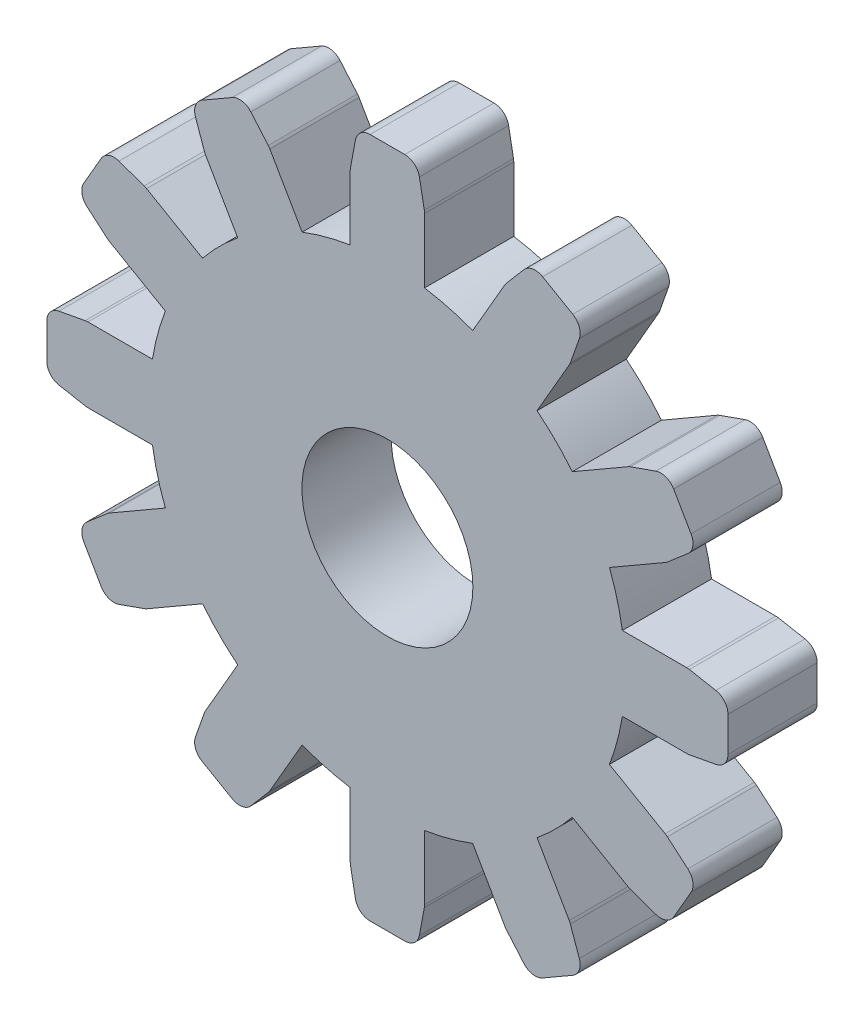
SolidWorks part; units mm, degrees
ref_plane "Front Plane" through (0, 0, 0) normal (0, 0, 1) x (1, 0, 0)
ref_plane "Top Plane" through (0, 0, 0) normal (0, 1, 0) x (1, 0, 0)
ref_plane "Right Plane" through (0, 0, 0) normal (1, 0, 0) x (0, 0, -1)
sketch "Sketch1" plane through (0, 0, 0) normal (0, 0, 1) x (1, 0, 0)
  line L0 (0, 0) -> (14.9711, 0) construction
  line L1 (0, 0) -> (0, 29.8184) construction
  line L2 (-1, 11.4548) -> (1, 11.4548)
  line L4 (-1.25, 10.1102) -> (-1.25, 7.9017)
  line L6 (1.25, 10.1187) -> (1.25, 7.9017)
  line L7 (3.9726, 9.3807) -> (2.8683, 7.4681)
  line L8 (4.8614, 10.4202) -> (3.9726, 9.3807)
  line L9 (-1, 11.4548) -> (-1.25, 10.1102)
  line L10 (1, 11.4548) -> (1.25, 10.1187)
  line L11 (4.8614, 10.4202) -> (6.5934, 9.4202)
  line L12 (6.5934, 9.4202) -> (6.1419, 8.1381)
  line L13 (6.1419, 8.1381) -> (5.0334, 6.2181)
  line L14 (8.1307, 6.1376) -> (6.2181, 5.0334)
  line L15 (9.4202, 6.5934) -> (8.1307, 6.1376)
  line L16 (9.4202, 6.5934) -> (10.4202, 4.8614)
  line L17 (10.4202, 4.8614) -> (9.3881, 3.9768)
  line L18 (9.3881, 3.9768) -> (7.4681, 2.8683)
  line L19 (10.1102, 1.25) -> (7.9017, 1.25)
  line L20 (11.4548, 1) -> (10.1102, 1.25)
  line L21 (11.4548, 1) -> (11.4548, -1)
  line L22 (11.4548, -1) -> (10.1187, -1.25)
  line L23 (10.1187, -1.25) -> (7.9017, -1.25)
  line L24 (9.3807, -3.9726) -> (7.4681, -2.8683)
  line L25 (10.4202, -4.8614) -> (9.3807, -3.9726)
  line L26 (10.4202, -4.8614) -> (9.4202, -6.5934)
  line L27 (9.4202, -6.5934) -> (8.1381, -6.1419)
  line L28 (8.1381, -6.1419) -> (6.2181, -5.0334)
  line L29 (6.1376, -8.1307) -> (5.0334, -6.2181)
  line L30 (6.5934, -9.4202) -> (6.1376, -8.1307)
  line L31 (6.5934, -9.4202) -> (4.8614, -10.4202)
  line L32 (4.8614, -10.4202) -> (3.9768, -9.3881)
  line L33 (3.9768, -9.3881) -> (2.8683, -7.4681)
  line L34 (1.25, -10.1102) -> (1.25, -7.9017)
  line L35 (1, -11.4548) -> (1.25, -10.1102)
  line L36 (1, -11.4548) -> (-1, -11.4548)
  line L37 (-1, -11.4548) -> (-1.25, -10.1187)
  line L38 (-1.25, -10.1187) -> (-1.25, -7.9017)
  line L39 (-3.9726, -9.3807) -> (-2.8683, -7.4681)
  line L40 (-4.8614, -10.4202) -> (-3.9726, -9.3807)
  line L41 (-4.8614, -10.4202) -> (-6.5934, -9.4202)
  line L42 (-6.5934, -9.4202) -> (-6.1419, -8.1381)
  line L43 (-6.1419, -8.1381) -> (-5.0334, -6.2181)
  line L44 (-8.1307, -6.1376) -> (-6.2181, -5.0334)
  line L45 (-9.4202, -6.5934) -> (-8.1307, -6.1376)
  line L46 (-9.4202, -6.5934) -> (-10.4202, -4.8614)
  line L47 (-10.4202, -4.8614) -> (-9.3881, -3.9768)
  line L48 (-9.3881, -3.9768) -> (-7.4681, -2.8683)
  line L49 (-10.1102, -1.25) -> (-7.9017, -1.25)
  line L50 (-11.4548, -1) -> (-10.1102, -1.25)
  line L51 (-11.4548, -1) -> (-11.4548, 1)
  line L52 (-11.4548, 1) -> (-10.1187, 1.25)
  line L53 (-10.1187, 1.25) -> (-7.9017, 1.25)
  line L54 (-9.3807, 3.9726) -> (-7.4681, 2.8683)
  line L55 (-10.4202, 4.8614) -> (-9.3807, 3.9726)
  line L56 (-10.4202, 4.8614) -> (-9.4202, 6.5934)
  line L57 (-9.4202, 6.5934) -> (-8.1381, 6.1419)
  line L58 (-8.1381, 6.1419) -> (-6.2181, 5.0334)
  line L59 (-6.1376, 8.1307) -> (-5.0334, 6.2181)
  line L60 (-6.5934, 9.4202) -> (-6.1376, 8.1307)
  line L61 (-6.5934, 9.4202) -> (-4.8614, 10.4202)
  line L62 (-4.8614, 10.4202) -> (-3.9768, 9.3881)
  line L63 (-3.9768, 9.3881) -> (-2.8683, 7.4681)
  arc A0 (2.8683, 7.4681) -> (1.25, 7.9017) centre (0, 0) ccw
  circle A1 centre (0, 0) radius 2.875
  arc A2 (-1.25, 7.9017) -> (-2.8683, 7.4681) centre (0, 0) ccw
  arc A3 (6.2181, 5.0334) -> (5.0334, 6.2181) centre (0, 0) ccw
  arc A4 (7.9017, 1.25) -> (7.4681, 2.8683) centre (0, 0) ccw
  arc A5 (7.4681, -2.8683) -> (7.9017, -1.25) centre (0, 0) ccw
  arc A6 (5.0334, -6.2181) -> (6.2181, -5.0334) centre (0, 0) ccw
  arc A7 (1.25, -7.9017) -> (2.8683, -7.4681) centre (0, 0) ccw
  arc A8 (-2.8683, -7.4681) -> (-1.25, -7.9017) centre (0, 0) ccw
  arc A9 (-6.2181, -5.0334) -> (-5.0334, -6.2181) centre (0, 0) ccw
  arc A10 (-7.9017, -1.25) -> (-7.4681, -2.8683) centre (0, 0) ccw
  arc A11 (-7.4681, 2.8683) -> (-7.9017, 1.25) centre (0, 0) ccw
  arc A12 (-5.0334, 6.2181) -> (-6.2181, 5.0334) centre (0, 0) ccw
  point P6 (0, 8)
  point P14 (0, 11.4548)
  point P82 (0, 0)
  dimension "D1" = 5.75
  dimension "D6" = 8
  dimension "D2" = 1.25
  dimension "D3" = 1.25
  dimension "D4" = 2
  dimension "D5" = 12
extrude "Boss-Extrude1" add sketch "Sketch1" along normal blind 3
fillet "Fillet1" radius 0.5 1 edges at (1, 11.4548, 1.5)
fillet "Fillet2" radius 0.5 1 edges at (-1, 11.4548, 1.5)
fillet "Fillet3" radius 0.5 1 edges at (6.5934, 9.4202, 1.5)
fillet "Fillet4" radius 0.5 1 edges at (4.8614, 10.4202, 1.5)
fillet "Fillet5" radius 0.5 1 edges at (9.4202, 6.5934, 1.5)
fillet "Fillet6" radius 0.5 1 edges at (10.4202, 4.8614, 1.5)
fillet "Fillet7" radius 0.5 1 edges at (11.4548, 1, 1.5)
fillet "Fillet8" radius 0.5 1 edges at (11.4548, -1, 1.5)
fillet "Fillet9" radius 0.5 1 edges at (10.4202, -4.8614, 1.5)
fillet "Fillet10" radius 0.5 1 edges at (9.4202, -6.5934, 1.5)
fillet "Fillet11" radius 0.5 1 edges at (6.5934, -9.4202, 1.5)
fillet "Fillet12" radius 0.5 1 edges at (4.8614, -10.4202, 1.5)
fillet "Fillet13" radius 0.5 1 edges at (1, -11.4548, 1.5)
fillet "Fillet14" radius 0.5 1 edges at (-1, -11.4548, 1.5)
fillet "Fillet15" radius 0.5 1 edges at (-4.8614, -10.4202, 1.5)
fillet "Fillet16" radius 0.5 1 edges at (-6.5934, -9.4202, 1.5)
fillet "Fillet17" radius 0.5 1 edges at (-9.4202, -6.5934, 1.5)
fillet "Fillet18" radius 0.5 1 edges at (-11.4548, 1, 1.5)
fillet "Fillet19" radius 0.5 1 edges at (-10.4202, 4.8614, 1.5)
fillet "Fillet20" radius 0.5 1 edges at (-4.8614, 10.4202, 1.5)
fillet "Fillet21" radius 0.5 1 edges at (-1.25, 10.1102, 1.5)
fillet "Fillet22" radius 0.5 1 edges at (1.25, 10.1187, 1.5)
fillet "Fillet23" radius 0.5 1 edges at (3.9726, 9.3807, 1.5)
fillet "Fillet24" radius 0.5 1 edges at (6.1419, 8.1381, 1.5)
fillet "Fillet25" radius 0.5 1 edges at (8.1307, 6.1376, 1.5)
fillet "Fillet26" radius 0.5 1 edges at (9.3881, 3.9768, 1.5)
fillet "Fillet27" radius 0.5 1 edges at (10.1102, 1.25, 1.5)
fillet "Fillet28" radius 0.5 1 edges at (10.1187, -1.25, 1.5)
fillet "Fillet29" radius 0.5 1 edges at (9.3807, -3.9726, 1.5)
fillet "Fillet30" radius 0.5 1 edges at (8.1381, -6.1419, 1.5)
fillet "Fillet31" radius 0.5 1 edges at (3.9768, -9.3881, 1.5)
fillet "Fillet32" radius 0.5 1 edges at (6.1376, -8.1307, 1.5)
fillet "Fillet33" radius 0.5 1 edges at (1.25, -10.1102, 1.5)
fillet "Fillet34" radius 0.5 2 edges at (-3.9726, -9.3807, 1.5) (-1.25, -10.1187, 1.5)
fillet "Fillet35" radius 0.5 1 edges at (-9.3881, -3.9768, 1.5)
fillet "Fillet36" radius 0.5 2 edges at (-11.4548, -1, 1.5) (-8.1307, -6.1376, 1.5)
fillet "Fillet41" radius 0.5 1 edges at (-6.5934, 9.4202, 1.5)
fillet "Fillet42" radius 0.5 1 edges at (-6.1376, 8.1307, 1.5)
fillet "Fillet43" radius 0.5 1 edges at (-8.1381, 6.1419, 1.5)
fillet "Fillet44" radius 0.5 1 edges at (-9.4202, 6.5934, 1.5)
fillet "Fillet45" radius 0.5 1 edges at (-3.9768, 9.3881, 1.5)
fillet "Fillet46" radius 0.5 1 edges at (-10.4202, -4.8614, 1.5)
fillet "Fillet47" radius 0.5 1 edges at (-10.1187, 1.25, 1.5)
fillet "Fillet48" radius 0.5 1 edges at (-10.1102, -1.25, 1.5)
